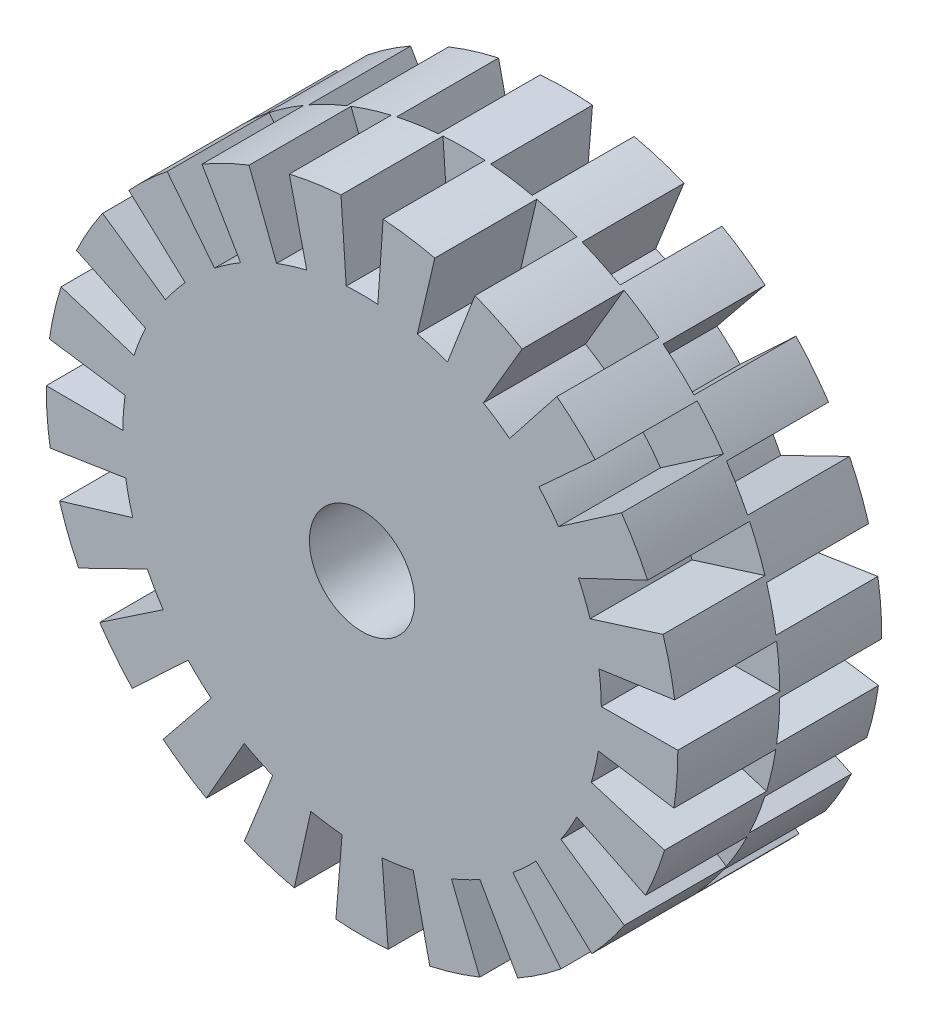
SolidWorks part; units mm, degrees
ref_plane "Plan de face" through (0, 0, 0) normal (0, 0, 1) x (1, 0, 0)
ref_plane "Plan de dessus" through (0, 0, 0) normal (0, 1, 0) x (1, 0, 0)
ref_plane "Plan de droite" through (0, 0, 0) normal (1, 0, 0) x (0, 0, -1)
sketch "Esquisse1" plane through (0, 0, 0) normal (0, 0, 1) x (1, 0, 0)
  circle A0 centre (0, 0) radius 12
  circle A1 centre (0, 0) radius 2
  dimension "D1" = 24
  dimension "D2" = 4
extrude "Boss.-Extru.1" add sketch "Esquisse1" along normal blind 7.75
sketch "Esquisse2" plane through (0, 0, 7.75) normal (0, 0, 1) x (1, 0, 0)
  line L0 (-0.8, 11.9733) -> (-0.6, 9.0733) construction
  line L1 (-0.6, 9.0733) -> (0.6, 9.0733) construction
  line L2 (0.8, 11.9733) -> (0.6, 9.0733) construction
  line L3 (-0.8, 11.9733) -> (-0.6, 9.0733)
  line L4 (-0.8, 11.9733) -> (0.8, 11.9733) construction
  line L5 (0, 11.9733) -> (0, 0) construction
  line L6 (0.6, 9.0733) -> (0.8, 11.9733)
  line L7 (-0.8, 11.9733) -> (-1.2164, 18.0106)
  line L8 (-1.2164, 18.0106) -> (1.2164, 18.0106)
  line L9 (1.2164, 18.0106) -> (0.8, 11.9733)
  line L10 (2.7647, 11.6772) -> (2.1011, 8.8471)
  line L11 (2.7647, 11.6772) -> (4.1464, 17.5689)
  line L12 (4.1464, 17.5689) -> (6.471, 16.8519)
  line L13 (6.471, 16.8519) -> (4.2937, 11.2056)
  line L14 (3.2477, 8.4933) -> (4.2937, 11.2056)
  line L15 (6.0838, 10.3435) -> (4.6154, 7.8347)
  line L16 (6.0838, 10.3435) -> (9.1407, 15.5662)
  line L17 (9.1407, 15.5662) -> (11.1507, 14.1958)
  line L18 (11.1507, 14.1958) -> (7.4058, 9.4422)
  line L19 (5.6069, 7.1587) -> (7.4058, 9.4422)
  line L20 (8.8623, 8.0907) -> (6.7197, 6.1262)
  line L21 (8.8623, 8.0907) -> (13.3228, 12.1804)
  line L22 (13.3228, 12.1804) -> (14.8396, 10.2784)
  line L23 (14.8396, 10.2784) -> (9.8599, 6.8398)
  line L24 (7.4679, 5.188) -> (9.8599, 6.8398)
  line L25 (10.8534, 5.119) -> (8.2269, 3.8734)
  line L26 (10.8534, 5.119) -> (16.3212, 7.7123)
  line L27 (16.3212, 7.7123) -> (17.21, 5.4477)
  line L28 (17.21, 5.4477) -> (11.4379, 3.6296)
  line L29 (8.6653, 2.7563) -> (11.4379, 3.6296)
  line L30 (11.88, 1.6925) -> (9.0031, 1.2764)
  line L31 (11.88, 1.6925) -> (17.8693, 2.5589)
  line L32 (17.8693, 2.5589) -> (18.0511, 0.133)
  line L33 (18.0511, 0.133) -> (11.9996, 0.097)
  line L34 (9.0928, 0.0797) -> (11.9996, 0.097)
  line L35 (11.8511, -1.8844) -> (8.9793, -1.434)
  line L36 (11.8511, -1.8844) -> (17.8297, -2.8219)
  line L37 (17.8297, -2.8219) -> (17.2883, -5.1936)
  line L38 (17.2883, -5.1936) -> (11.4951, -3.4443)
  line L39 (8.7123, -2.604) -> (11.4951, -3.4443)
  line L40 (10.7692, -5.2938) -> (8.1577, -4.017)
  line L41 (10.7692, -5.2938) -> (16.2058, -7.9519)
  line L42 (16.2058, -7.9519) -> (14.9894, -10.0587)
  line L43 (14.9894, -10.0587) -> (9.9692, -6.6795)
  line L44 (7.5577, -5.0563) -> (9.9692, -6.6795)
  line L45 (8.7304, -8.2329) -> (6.6112, -6.2431)
  line L46 (8.7304, -8.2329) -> (13.142, -12.3753)
  line L47 (13.142, -12.3753) -> (11.3586, -14.03)
  line L48 (11.3586, -14.03) -> (7.5575, -9.3212)
  line L49 (5.7316, -7.0593) -> (7.5575, -9.3212)
  line L50 (5.9158, -10.4405) -> (4.4773, -7.9144)
  line L51 (5.9158, -10.4405) -> (8.9104, -15.6992)
  line L52 (8.9104, -15.6992) -> (6.7186, -16.7547)
  line L53 (6.7186, -16.7547) -> (4.4742, -11.1347)
  line L54 (3.3962, -8.4351) -> (4.4742, -11.1347)
  line L55 (2.5756, -11.7203) -> (1.9456, -8.8825)
  line L56 (2.5756, -11.7203) -> (3.8871, -17.6281)
  line L57 (3.8871, -17.6281) -> (1.4816, -17.9907)
  line L58 (1.4816, -17.9907) -> (0.9935, -11.9588)
  line L59 (0.759, -9.0614) -> (0.9935, -11.9588)
  line L60 (-0.9935, -11.9588) -> (-0.759, -9.0614)
  line L61 (-0.9935, -11.9588) -> (-1.4816, -17.9907)
  line L62 (-1.4816, -17.9907) -> (-3.8871, -17.6281)
  line L63 (-3.8871, -17.6281) -> (-2.5756, -11.7203)
  line L64 (-1.9456, -8.8825) -> (-2.5756, -11.7203)
  line L65 (-4.4742, -11.1347) -> (-3.3962, -8.4351)
  line L66 (-4.4742, -11.1347) -> (-6.7186, -16.7547)
  line L67 (-6.7186, -16.7547) -> (-8.9104, -15.6992)
  line L68 (-8.9104, -15.6992) -> (-5.9158, -10.4405)
  line L69 (-4.4773, -7.9144) -> (-5.9158, -10.4405)
  line L70 (-7.5575, -9.3212) -> (-5.7316, -7.0593)
  line L71 (-7.5575, -9.3212) -> (-11.3586, -14.03)
  line L72 (-11.3586, -14.03) -> (-13.142, -12.3753)
  line L73 (-13.142, -12.3753) -> (-8.7304, -8.2329)
  line L74 (-6.6112, -6.2431) -> (-8.7304, -8.2329)
  line L75 (-9.9692, -6.6795) -> (-7.5577, -5.0563)
  line L76 (-9.9692, -6.6795) -> (-14.9894, -10.0587)
  line L77 (-14.9894, -10.0587) -> (-16.2058, -7.9519)
  line L78 (-16.2058, -7.9519) -> (-10.7692, -5.2938)
  line L79 (-8.1577, -4.017) -> (-10.7692, -5.2938)
  line L80 (-11.4951, -3.4443) -> (-8.7123, -2.604)
  line L81 (-11.4951, -3.4443) -> (-17.2883, -5.1936)
  line L82 (-17.2883, -5.1936) -> (-17.8297, -2.8219)
  line L83 (-17.8297, -2.8219) -> (-11.8511, -1.8844)
  line L84 (-8.9793, -1.434) -> (-11.8511, -1.8844)
  line L85 (-11.9996, 0.097) -> (-9.0928, 0.0797)
  line L86 (-11.9996, 0.097) -> (-18.0511, 0.133)
  line L87 (-18.0511, 0.133) -> (-17.8693, 2.5589)
  line L88 (-17.8693, 2.5589) -> (-11.88, 1.6925)
  line L89 (-9.0031, 1.2764) -> (-11.88, 1.6925)
  line L90 (-11.4379, 3.6296) -> (-8.6653, 2.7563)
  line L91 (-11.4379, 3.6296) -> (-17.21, 5.4477)
  line L92 (-17.21, 5.4477) -> (-16.3212, 7.7123)
  line L93 (-16.3212, 7.7123) -> (-10.8534, 5.119)
  line L94 (-8.2269, 3.8734) -> (-10.8534, 5.119)
  line L95 (-9.8599, 6.8398) -> (-7.4679, 5.188)
  line L96 (-9.8599, 6.8398) -> (-14.8396, 10.2784)
  line L97 (-14.8396, 10.2784) -> (-13.3228, 12.1804)
  line L98 (-13.3228, 12.1804) -> (-8.8623, 8.0907)
  line L99 (-6.7197, 6.1262) -> (-8.8623, 8.0907)
  line L100 (-7.4058, 9.4422) -> (-5.6069, 7.1587)
  line L101 (-7.4058, 9.4422) -> (-11.1507, 14.1958)
  line L102 (-11.1507, 14.1958) -> (-9.1407, 15.5662)
  line L103 (-9.1407, 15.5662) -> (-6.0838, 10.3435)
  line L104 (-4.6154, 7.8347) -> (-6.0838, 10.3435)
  line L105 (-4.2937, 11.2056) -> (-3.2477, 8.4933)
  line L106 (-4.2937, 11.2056) -> (-6.471, 16.8519)
  line L107 (-6.471, 16.8519) -> (-4.1464, 17.5689)
  line L108 (-4.1464, 17.5689) -> (-2.7647, 11.6772)
  line L109 (-2.1011, 8.8471) -> (-2.7647, 11.6772)
  circle A1 centre (0, 0) radius 12 construction
  arc A2 (0.6, 9.0733) -> (-0.6, 9.0733) centre (0, 0) ccw
  arc A3 (3.2477, 8.4933) -> (2.1011, 8.8471) centre (0, 0) ccw
  arc A4 (5.6069, 7.1587) -> (4.6154, 7.8347) centre (0, 0) ccw
  arc A5 (7.4679, 5.188) -> (6.7197, 6.1262) centre (0, 0) ccw
  arc A6 (8.6653, 2.7563) -> (8.2269, 3.8734) centre (0, 0) ccw
  arc A7 (9.0928, 0.0797) -> (9.0031, 1.2764) centre (0, 0) ccw
  arc A8 (8.7123, -2.604) -> (8.9793, -1.434) centre (0, 0) ccw
  arc A9 (7.5577, -5.0563) -> (8.1577, -4.017) centre (0, 0) ccw
  arc A10 (5.7316, -7.0593) -> (6.6112, -6.2431) centre (0, 0) ccw
  arc A11 (3.3962, -8.4351) -> (4.4773, -7.9144) centre (0, 0) ccw
  arc A12 (0.759, -9.0614) -> (1.9456, -8.8825) centre (0, 0) ccw
  arc A13 (-1.9456, -8.8825) -> (-0.759, -9.0614) centre (0, 0) ccw
  arc A14 (-4.4773, -7.9144) -> (-3.3962, -8.4351) centre (0, 0) ccw
  arc A15 (-6.6112, -6.2431) -> (-5.7316, -7.0593) centre (0, 0) ccw
  arc A16 (-8.1577, -4.017) -> (-7.5577, -5.0563) centre (0, 0) ccw
  arc A17 (-8.9793, -1.434) -> (-8.7123, -2.604) centre (0, 0) ccw
  arc A18 (-9.0031, 1.2764) -> (-9.0928, 0.0797) centre (0, 0) ccw
  arc A19 (-8.2269, 3.8734) -> (-8.6653, 2.7563) centre (0, 0) ccw
  arc A20 (-6.7197, 6.1262) -> (-7.4679, 5.188) centre (0, 0) ccw
  arc A21 (-4.6154, 7.8347) -> (-5.6069, 7.1587) centre (0, 0) ccw
  arc A22 (-2.1011, 8.8471) -> (-3.2477, 8.4933) centre (0, 0) ccw
  point P1 (0, 9.0733)
  point P134 (0, 0)
  dimension "D1" = 2.9
  dimension "D2" = 1.2
  dimension "D3" = 21
  dimension "D4" = 1.6
extrude "Enlèv. mat.-Extru.1" cut sketch "Esquisse2" against normal blind 3.875
sketch "Esquisse3" plane through (0, 0, 0) normal (0, 0, -1) x (-1, 0, 0)
  line L0 (0, 0) -> (2.0891, 13.9787) construction
  line L1 (0.9786, 11.96) -> (2.561, 11.7235) construction
  line L2 (1.1507, 14.119) -> (0.7474, 9.06)
  line L3 (1.1507, 14.119) -> (3.0276, 13.8385)
  line L4 (3.0276, 13.8385) -> (1.9342, 8.8827)
  line L5 (0, 0) -> (17.443, 0) construction
  line L6 (5.2612, 13.1526) -> (3.3847, 8.4372)
  line L7 (5.2612, 13.1526) -> (6.9721, 12.3313)
  line L8 (6.9721, 12.3313) -> (4.4665, 7.9179)
  line L9 (8.9042, 11.0175) -> (5.7212, 7.0647)
  line L10 (8.9042, 11.0175) -> (10.297, 9.7284)
  line L11 (10.297, 9.7284) -> (6.6019, 6.2496)
  line L12 (11.7561, 7.9034) -> (7.5494, 5.0645)
  line L13 (11.7561, 7.9034) -> (12.7071, 6.2611)
  line L14 (12.7071, 6.2611) -> (8.1507, 4.026)
  line L15 (13.5634, 4.0871) -> (8.7068, 2.6143)
  line L16 (13.5634, 4.0871) -> (13.988, 2.2374)
  line L17 (13.988, 2.2374) -> (8.9753, 1.4447)
  line L18 (14.1655, -0.0923) -> (9.0906, -0.0682)
  line L19 (14.1655, -0.0923) -> (14.0261, -1.985)
  line L20 (14.0261, -1.985) -> (9.0024, -1.265)
  line L21 (13.509, -4.2636) -> (8.6666, -2.7447)
  line L22 (13.509, -4.2636) -> (12.8178, -6.0311)
  line L23 (12.8178, -6.0311) -> (8.2296, -3.8623)
  line L24 (11.6521, -8.056) -> (7.4725, -5.1773)
  line L25 (11.6521, -8.056) -> (10.4707, -9.5412)
  line L26 (10.4707, -9.5412) -> (6.7255, -6.1164)
  line L27 (8.7599, -11.1326) -> (5.6145, -7.1498)
  line L28 (8.7599, -11.1326) -> (7.1932, -12.2036)
  line L29 (7.1932, -12.2036) -> (4.6239, -7.827)
  line L30 (5.0893, -13.22) -> (3.2576, -8.4871)
  line L31 (5.0893, -13.22) -> (3.2765, -13.7817)
  line L32 (3.2765, -13.7817) -> (2.1114, -8.8422)
  line L33 (0.9665, -14.1328) -> (0.6113, -9.0702)
  line L34 (0.9665, -14.1328) -> (-0.9313, -14.1352)
  line L35 (-0.9313, -14.1352) -> (-0.5887, -9.0717)
  line L36 (-3.2421, -13.7898) -> (-2.0893, -8.8475)
  line L37 (-3.2421, -13.7898) -> (-5.0563, -13.2327)
  line L38 (-5.0563, -13.2327) -> (-3.2365, -8.4952)
  line L39 (-7.1627, -12.2215) -> (-4.6044, -7.8385)
  line L40 (-7.1627, -12.2215) -> (-8.7321, -11.1544)
  line L41 (-8.7321, -11.1544) -> (-5.5967, -7.1638)
  line L42 (-10.4469, -9.5673) -> (-6.7102, -6.1331)
  line L43 (-10.4469, -9.5673) -> (-11.632, -8.085)
  line L44 (-11.632, -8.085) -> (-7.4596, -5.1959)
  line L45 (-12.8028, -6.063) -> (-8.2199, -3.8828)
  line L46 (-12.8028, -6.063) -> (-13.4983, -4.2973)
  line L47 (-13.4983, -4.2973) -> (-8.6597, -2.7663)
  line L48 (-14.0211, -2.02) -> (-8.9992, -1.2874)
  line L49 (-14.0211, -2.02) -> (-14.1652, -0.1277)
  line L50 (-14.1652, -0.1277) -> (-9.0904, -0.0909)
  line L51 (-13.9935, 2.2026) -> (-8.9789, 1.4223)
  line L52 (-13.9935, 2.2026) -> (-13.5735, 4.0533)
  line L53 (-13.5735, 4.0533) -> (-8.7133, 2.5926)
  line L54 (-12.7226, 6.2294) -> (-8.1607, 4.0057)
  line L55 (-12.7226, 6.2294) -> (-11.7758, 7.8741)
  line L56 (-11.7758, 7.8741) -> (-7.562, 5.0457)
  line L57 (-10.3213, 9.7027) -> (-6.6174, 6.2332)
  line L58 (-10.3213, 9.7027) -> (-8.9317, 10.9952)
  line L59 (-8.9317, 10.9952) -> (-5.7388, 7.0505)
  line L60 (-7.0028, 12.3139) -> (-4.4862, 7.9068)
  line L61 (-7.0028, 12.3139) -> (-5.294, 13.1394)
  line L62 (-5.294, 13.1394) -> (-3.4057, 8.4288)
  line L63 (-3.0621, 13.8309) -> (-1.9563, 8.8778)
  line L64 (-3.0621, 13.8309) -> (-1.1859, 14.1161)
  line L65 (-1.1859, 14.1161) -> (-0.77, 9.0581)
  arc A0 (1.9342, 8.8827) -> (0.7474, 9.06) centre (0, 0) ccw
  circle A1 centre (0, 0) radius 12 construction
  arc A2 (4.4665, 7.9179) -> (3.3847, 8.4372) centre (0, 0) ccw
  arc A3 (6.6019, 6.2496) -> (5.7212, 7.0647) centre (0, 0) ccw
  arc A4 (8.1507, 4.026) -> (7.5494, 5.0645) centre (0, 0) ccw
  arc A5 (8.9753, 1.4447) -> (8.7068, 2.6143) centre (0, 0) ccw
  arc A6 (9.0024, -1.265) -> (9.0906, -0.0682) centre (0, 0) ccw
  arc A7 (8.2296, -3.8623) -> (8.6666, -2.7447) centre (0, 0) ccw
  arc A8 (6.7255, -6.1164) -> (7.4725, -5.1773) centre (0, 0) ccw
  arc A9 (4.6239, -7.827) -> (5.6145, -7.1498) centre (0, 0) ccw
  arc A10 (2.1114, -8.8422) -> (3.2576, -8.4871) centre (0, 0) ccw
  arc A11 (-0.5887, -9.0717) -> (0.6113, -9.0702) centre (0, 0) ccw
  arc A12 (-3.2365, -8.4952) -> (-2.0893, -8.8475) centre (0, 0) ccw
  arc A13 (-5.5967, -7.1638) -> (-4.6044, -7.8385) centre (0, 0) ccw
  arc A14 (-7.4596, -5.1959) -> (-6.7102, -6.1331) centre (0, 0) ccw
  arc A15 (-8.6597, -2.7663) -> (-8.2199, -3.8828) centre (0, 0) ccw
  arc A16 (-9.0904, -0.0909) -> (-8.9992, -1.2874) centre (0, 0) ccw
  arc A17 (-8.7133, 2.5926) -> (-8.9789, 1.4223) centre (0, 0) ccw
  arc A18 (-7.562, 5.0457) -> (-8.1607, 4.0057) centre (0, 0) ccw
  arc A19 (-5.7388, 7.0505) -> (-6.6174, 6.2332) centre (0, 0) ccw
  arc A20 (-3.4057, 8.4288) -> (-4.4862, 7.9068) centre (0, 0) ccw
  arc A21 (-0.77, 9.0581) -> (-1.9563, 8.8778) centre (0, 0) ccw
  point P6 (1.7698, 11.8418)
  point P98 (0, 0)
  dimension "D1" = 1.6
  dimension "D2" = 0.6
  dimension "D3" = 2.9
  dimension "D4" = 81.5
  dimension "D5" = 21
extrude "Enlèv. mat.-Extru.2" cut sketch "Esquisse3" against normal blind 3.875
sketch "Esquisse4" plane through (0, 0, 0) normal (0, 0, -1) x (-1, 0, 0)
  circle A0 centre (8.1117, 1.7398) radius 2.2962
  circle A1 centre (0, 0) radius 6
  circle A2 centre (0, 0) radius 4.75
  circle A3 centre (23.9745, -1.7282) radius 2.3315
  dimension "D1" = 9.5
  dimension "D2" = 12
